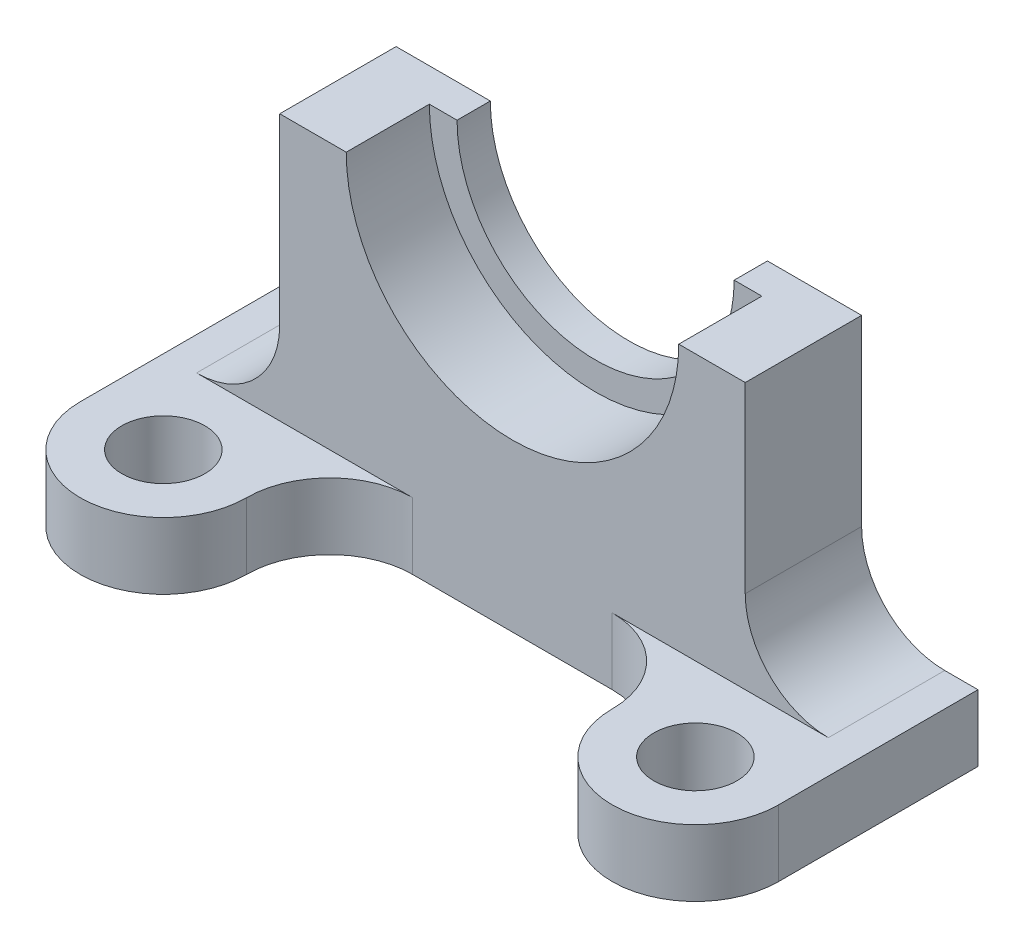
SolidWorks part; units mm, degrees
ref_plane "前基準面" through (0, 0, 0) normal (0, 0, 1) x (1, 0, 0)
ref_plane "上基準面" through (0, 0, 0) normal (0, 1, 0) x (1, 0, 0)
ref_plane "右基準面" through (0, 0, 0) normal (1, 0, 0) x (0, 0, -1)
sketch "草圖1" plane through (0, 0, 0) normal (0, 1, 0) x (1, 0, 0)
  line L0 (0, 0) -> (0, 72)
  line L1 (0, 72) -> (252, 72)
  line L2 (252, 72) -> (252, 0)
  line L3 (162, 30) -> (90, 30)
  line L4 (126, 30) -> (126, 163.1156) construction
  line L5 (0, 72) -> (0, 0)
  arc A0 (252, 0) -> (192, 0) centre (222, 0) cw
  arc A1 (192, 0) -> (162, 30) centre (162, 0) ccw
  arc A2 (60, 0) -> (90, 30) centre (90, 0) cw
  arc A3 (0, 0) -> (60, 0) centre (30, 0) ccw
  circle A4 centre (30, 0) radius 15
  circle A5 centre (222, 0) radius 15
  dimension "D1" = 30
  dimension "D2" = 72
  dimension "D3" = 30
  dimension "D4" = 30
  dimension "D5" = 192
  dimension "D6" = 42
extrude "填料-伸長1" add sketch "草圖1" along normal blind 24 contours L4 L3 A1 A0 L2 L1 A5 | L3 L4 L1 L0 A3 A2 A4
sketch "草圖3" plane through (0, 0, -72) normal (0, 0, -1) x (-1, 0, 0)
  line L0 (-210, 24) -> (-210, 120)
  line L1 (0, 24) -> (-252, 24) construction
  line L2 (-210, 120) -> (-42, 120)
  line L3 (-42, 120) -> (-42, 24)
  line L4 (-42, 24) -> (-210, 24)
  line L5 (0, 0) -> (-252, 0) construction
  line L6 (-126, 0) -> (-126, 56.3424) construction
  dimension "D1" = 168
  dimension "D2" = 120
extrude "填料-伸長2" add sketch "草圖3" against normal blind 42
sketch "草圖4" plane through (0, 0, -30) normal (0, 0, 1) x (1, 0, 0)
  line L0 (126, 120) -> (126, -35.1599) construction
  line L1 (42, 120) -> (210, 120) construction
  circle A0 centre (126, 120) radius 60
  dimension "D1" = 120
extrude "除料-伸長1" cut sketch "草圖4" against normal blind 30
sketch "草圖5" plane through (0, 0, -60) normal (0, 0, 1) x (1, 0, 0)
  line L0 (66, 120) -> (186, 120) construction
  circle A0 centre (126, 120) radius 50
  dimension "D1" = 100
extrude "除料-伸長2" cut sketch "草圖5" against normal blind 30
fillet "圓角1" radius 30 2 edges
